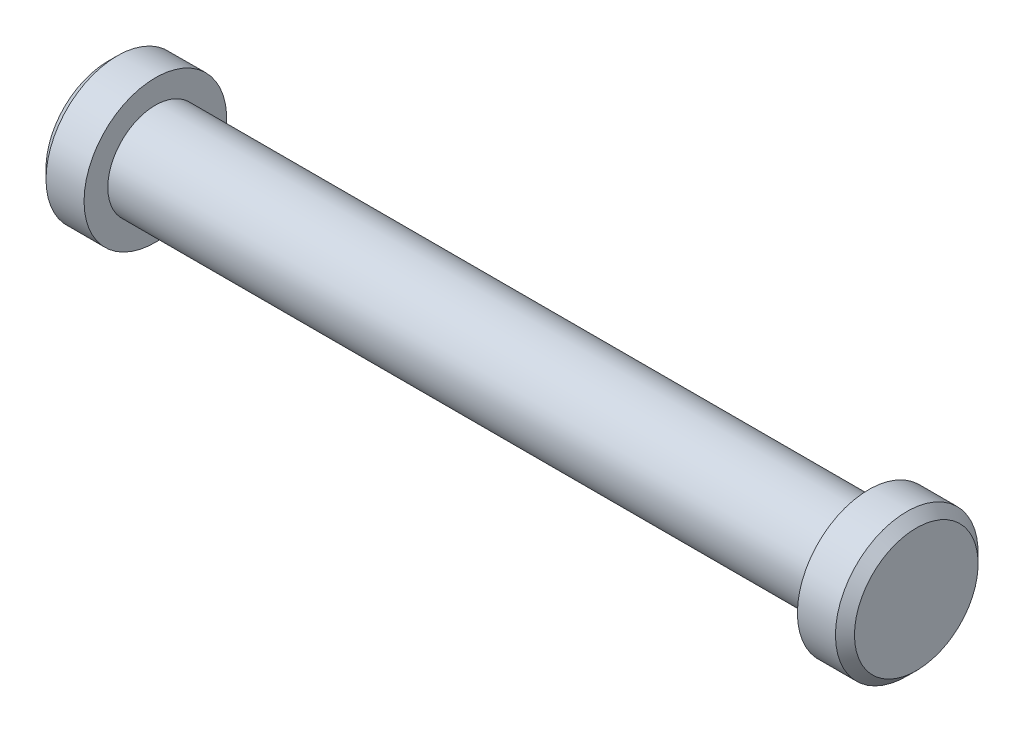
SolidWorks part; units mm, degrees
ref_plane "Front Plane" through (0, 0, 0) normal (0, 0, 1) x (1, 0, 0)
ref_plane "Top Plane" through (0, 0, 0) normal (0, 1, 0) x (1, 0, 0)
ref_plane "Right Plane" through (0, 0, 0) normal (1, 0, 0) x (0, 0, -1)
other "Configuration Table"
sketch "Sketch1" plane through (0, 0, 0) normal (0, 0, 1) x (1, 0, 0)
  line L0 (-10.795, 0) -> (10.795, 0) construction
  line L1 (-10.795, 0) -> (-10.795, 1.905)
  line L2 (-10.795, 1.905) -> (-9.525, 1.905)
  line L3 (-9.525, 1.905) -> (-9.525, 1.27)
  line L4 (-9.525, 1.27) -> (9.525, 1.27)
  line L5 (9.525, 1.27) -> (9.525, 1.905)
  line L6 (9.525, 1.905) -> (10.795, 1.905)
  line L7 (10.795, 1.905) -> (10.795, 0)
  line L8 (-10.795, 0) -> (10.795, 0)
  dimension "D1" = 19.05
  dimension "D2" = 2.54
  dimension "D3" = 3.81
  dimension "D4" = 1.27
revolve "Revolve1" add sketch "Sketch1" angle 360 about L0
chamfer "Chamfer1" distance 0.254 angle 45 2 edges at (-10.795, 0, 1.905) (10.795, 0, 1.905)
scale "Scale1" scale about centroid uniform scaling yes scale factor 1.5
